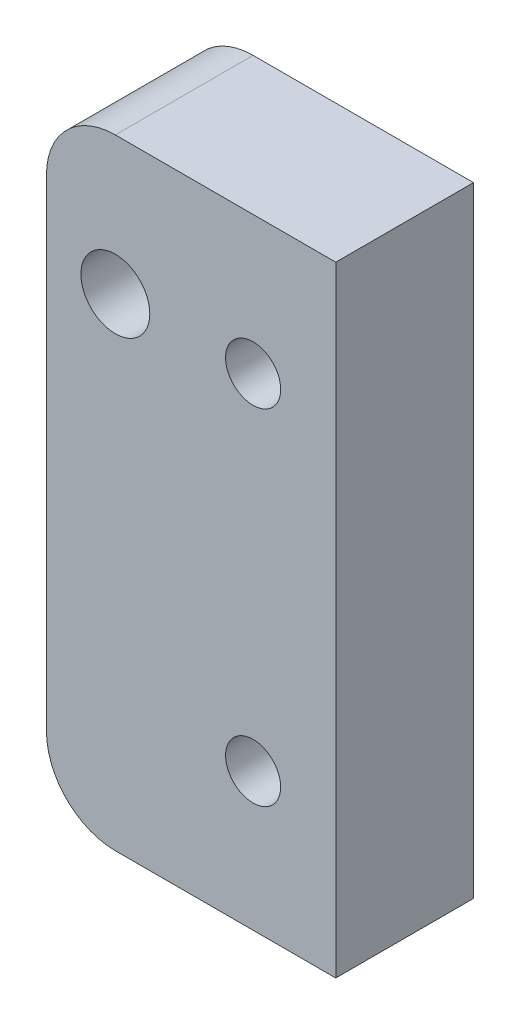
SolidWorks part; units mm, degrees
ref_plane "Plan de face" through (0, 0, 0) normal (0, 0, 1) x (1, 0, 0)
ref_plane "Plan de dessus" through (0, 0, 0) normal (0, 1, 0) x (1, 0, 0)
ref_plane "Plan de droite" through (0, 0, 0) normal (1, 0, 0) x (0, 0, -1)
sketch "Esquisse1" plane through (0, 0, 0) normal (0, 0, 1) x (1, 0, 0)
  line L1 (-28.1068, 17.8497) -> (-7.1068, 17.8497)
  line L2 (-28.1068, 17.8497) -> (-28.1068, -27.1503)
  line L3 (-28.1068, -27.1503) -> (-7.1068, -27.1503)
  line L4 (-7.1068, 17.8497) -> (-7.1068, -27.1503)
  dimension "D1" = 21
  dimension "D2" = 45
extrude "Boss.-Extru.1" add sketch "Esquisse1" along normal blind 10
sketch "Esquisse2" plane through (0, 0, 10) normal (0, 0, 1) x (1, 0, 0)
  line L1 (-28.1068, 17.8497) -> (-28.1068, -27.1503) construction
  circle A1 centre (-23.1068, 7.8497) radius 2.5
  point P4 (0, 0)
  point P10 (0, 0)
  point P11 (0, 0)
  dimension "D1" = 5
  dimension "D2" = 5
extrude "Enlèv. mat.-Extru.1" cut sketch "Esquisse2" against normal up to vertex (10 mm away)
sketch "Esquisse4" plane through (0, 0, 10) normal (0, 0, 1) x (1, 0, 0)
  line L1 (-7.1068, -27.1503) -> (-7.1068, 17.8497) construction
  line L2 (-7.1068, 17.8497) -> (-28.1068, 17.8497) construction
  circle A0 centre (-13.1068, 7.8497) radius 2
  circle A1 centre (-13.1068, -17.1503) radius 2
  point P4 (0, 0)
  dimension "D2" = 4
  dimension "D4" = 25
  dimension "D1" = 6
  dimension "D3" = 10
extrude "Enlèv. mat.-Extru.3" cut sketch "Esquisse4" against normal up to vertex (10 mm away)
fillet "Congé1" radius 5 2 edges at (-28.1068, 17.8497, 5) (-28.1068, -27.1503, 5)
sketch "Esquisse7" plane through (0, 0, 0) normal (0, 0, -1) x (-1, 0, 0)
  line L0 (15.8568, 9.4374) -> (13.1068, 11.0251)
  line L1 (13.1068, 11.0251) -> (10.3568, 9.4374)
  line L2 (10.3568, 9.4374) -> (10.3568, 6.262)
  line L3 (10.3568, 6.262) -> (13.1068, 4.6743)
  line L4 (13.1068, 4.6743) -> (15.8568, 6.262)
  line L5 (15.8568, 6.262) -> (15.8568, 9.4374)
  line L7 (7.1068, -27.1503) -> (7.1068, 17.8497) construction
  line L9 (15.8568, -15.5626) -> (13.1068, -13.9749)
  line L10 (13.1068, -13.9749) -> (10.3568, -15.5626)
  line L11 (10.3568, -15.5626) -> (10.3568, -18.738)
  line L12 (10.3568, -18.738) -> (13.1068, -20.3257)
  line L13 (13.1068, -20.3257) -> (15.8568, -18.738)
  line L14 (15.8568, -18.738) -> (15.8568, -15.5626)
  circle A0 centre (13.1068, 7.8497) radius 2.75 construction
  circle A1 centre (13.1068, -17.1503) radius 2.75 construction
  dimension "D1" = 5.5
extrude "Enlèv. mat.-Extru.6" cut sketch "Esquisse7" against normal blind 4
